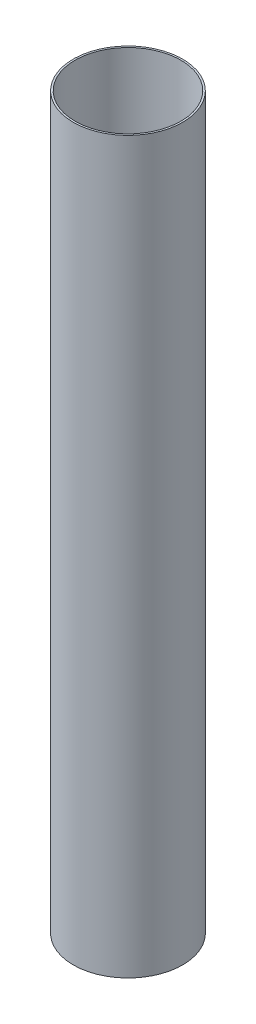
SolidWorks part; units mm, degrees
ref_plane "Front Plane" through (0, 0, 0) normal (0, 0, 1) x (1, 0, 0)
ref_plane "Top Plane" through (0, 0, 0) normal (0, 1, 0) x (1, 0, 0)
ref_plane "Right Plane" through (0, 0, 0) normal (1, 0, 0) x (0, 0, -1)
sketch "Sketch1" plane through (0, 0, 0) normal (0, 1, 0) x (1, 0, 0)
  circle A0 centre (0, 0) radius 38.1
  circle A1 centre (0, 0) radius 36.83
  dimension "D1" = 76.2
  dimension "D2" = 73.66
extrude "Boss-Extrude1" add sketch "Sketch1" along normal mid plane 508
equation "\"airframeInnerDiameter\"= 6in"
equation "\"outerDiameter\"= 6.112in"
equation "\"airframeBulkheadThickness\"= 0.125in"
equation "\"payloadAirframeLength\"= 10in"
equation "\"payloadInnerDiameter\"= 6in - 0.056in"
equation "\"payloadOuterDiameter\"= \"airframeInnerDiameter\""
equation "\"payloadLength\"= 11in"
equation "\"payloadBand\"= 2in"
equation "\"payloadOffsetFromAft\"= 6in"
equation "\"upperAirframeLength\"= 25in"
equation "\"recoveryBayInnerDiameter\"= 5.888in"
equation "\"recoveryLength\"= 8in"
equation "\"recoveryBand\"= 2in"
equation "\"recoveryCouplerOuter\"=\"airframeInnerDiameter\""
equation "\"recoveryOffsetFromAft\"= 3in"
equation "\"midAirframeLength\"= 20in"
equation "\"atsLength\"= 11in"
equation "\"atsInner\"= 5.888in"
equation "\"atsBand\"= 2in"
equation "\"atsCouplerOuter\"=\"airframeInnerDiameter\""
equation "\"atsOffsetFromAft\"= 3in"
equation "\"lowerAirframeLength\"= 40in"
equation "\"motorTubeOuterDiameter\"= 4.25in"
equation "\"motorTubeInnerDiameter\"= 4in"
equation "\"motorTubeLength\"= 32in"
equation "\"centeringRingOuterDiameter\"= \"airframeInnerDiameter\""
equation "\"centeringRingInnerDiameter\"= \"motorTubeOuterDiameter\""
equation "\"centeringRingThickness\"= 0.375in"
equation "\"topCenteringRingOffsetFromAft\"= 16.7in"
equation "\"bottomCenteringRingOffsetFromAft\"= 0.3in"
equation "\"finSlotLength\"= 8in"
equation "\"finSlotOffsetFromAft\"= 3in"
equation "\"finSlotWidth\"= 0.187in"
equation "\"motorCasingOuterDiameter\"= 3in"
equation "\"motorCasingCenteringRingThickness\"= 0.25in"
equation "\"D1@Sketch1\"=\"motorCasingOuterDiameter\""
